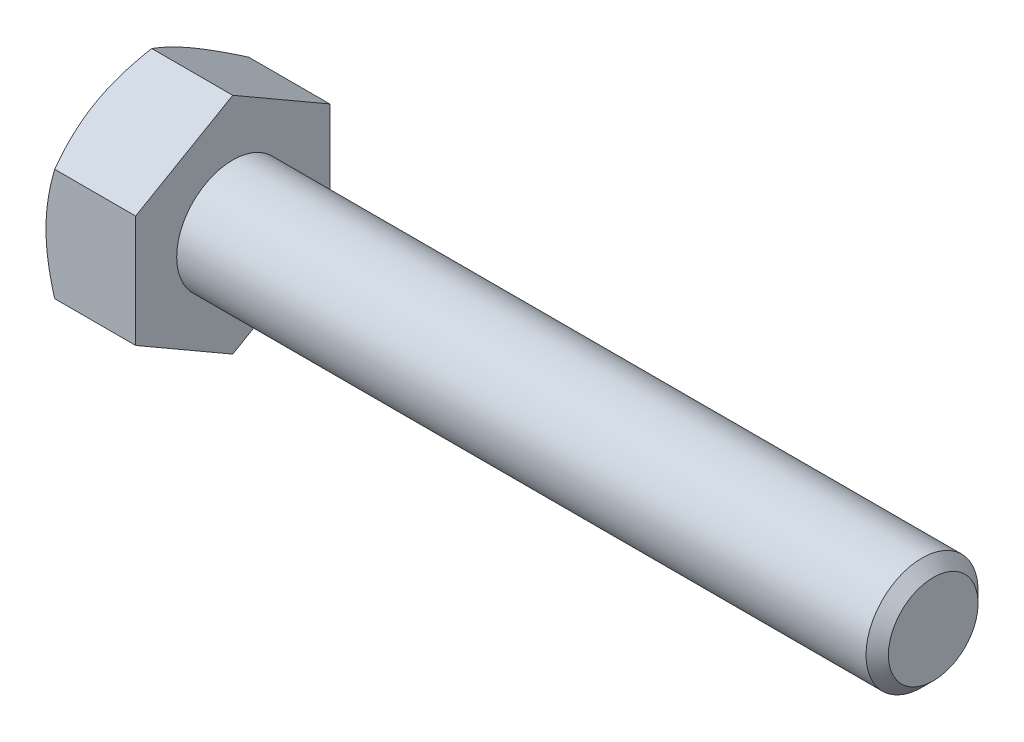
SolidWorks part; units mm, degrees
ref_plane "Front Plane" through (0, 0, 0) normal (0, 0, 1) x (1, 0, 0)
ref_plane "Top Plane" through (0, 0, 0) normal (0, 1, 0) x (1, 0, 0)
ref_plane "Right Plane" through (0, 0, 0) normal (1, 0, 0) x (0, 0, -1)
sketch "Sketch1" plane through (0, 0, 0) normal (1, 0, 0) x (0, 0, -1)
  line L1 (20.7846, -12) -> (20.7846, 12)
  line L2 (20.7846, 12) -> (0, 24)
  line L3 (0, 24) -> (-20.7846, 12)
  line L4 (-20.7846, 12) -> (-20.7846, -12)
  line L5 (-20.7846, -12) -> (0, -24)
  line L6 (0, -24) -> (20.7846, -12)
  circle A0 centre (0, 0) radius 20.7846 construction
extrude "Boss-Extrude1" add sketch "Sketch1" along normal blind 19.2
sketch "Sketch2" plane through (19.2, 0, 0) normal (1, 0, 0) x (0, 0, -1)
  circle A0 centre (0, 0) radius 12
  dimension "D1" = 24
extrude "Boss-Extrude2" add sketch "Sketch2" along normal blind 150
cosmetic thread "Cosmetic Thread2" parameters "D1"=60, "D2"=20.704
sketch "Sketch3" plane through (0, 0, 0) normal (-1, 0, 0) x (0, 0, 1)
  circle A0 centre (0, 0) radius 20.7846
extrude "Cut-Extrude1" cut sketch "Sketch3" against normal blind 19.2 draft 60 flip side to cut
chamfer "Chamfer1" distance 2.4 angle 45 1 edges at (169.2, 0, -12)
